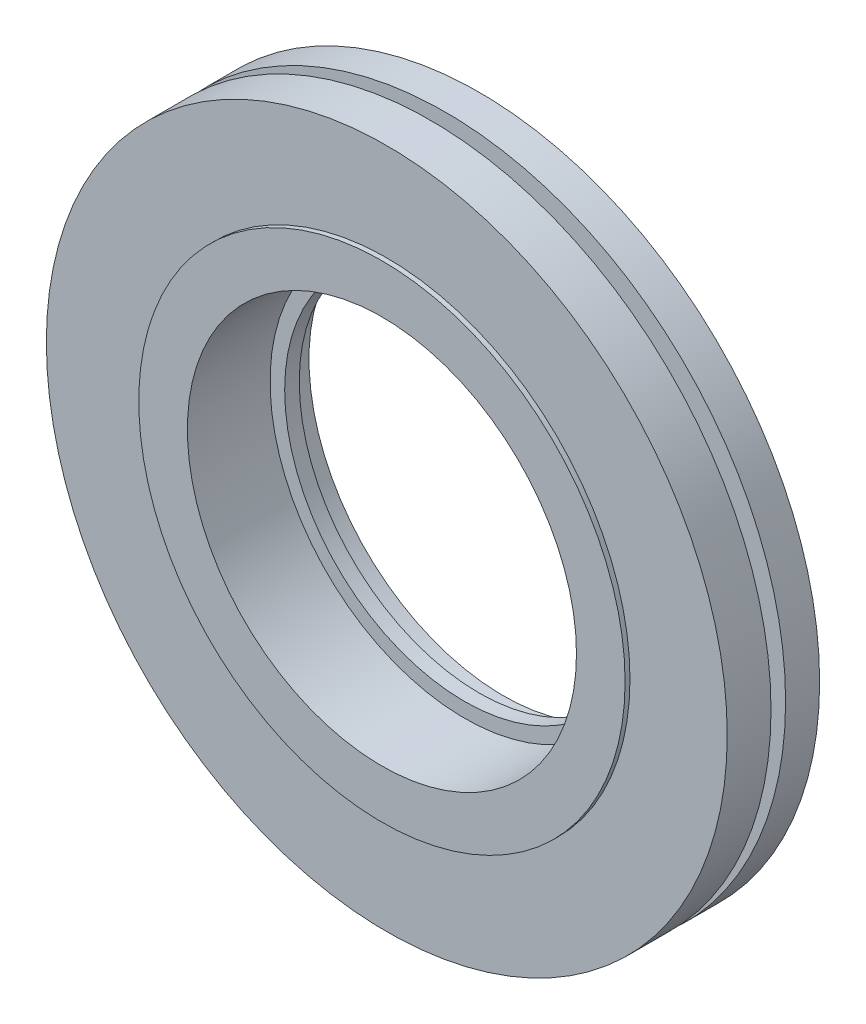
SolidWorks part; units mm, degrees
material "7075-T6 (SN)"
ref_plane "Front Plane" through (0, 0, 0) normal (0, 0, 1) x (1, 0, 0)
ref_plane "Top Plane" through (0, 0, 0) normal (0, 1, 0) x (1, 0, 0)
ref_plane "Right Plane" through (0, 0, 0) normal (1, 0, 0) x (0, 0, -1)
sketch "Sketch1" plane through (0, 0, 0) normal (0, 0, 1) x (1, 0, 0)
  circle A0 centre (0, 0) radius 5
  circle A1 centre (0, 0) radius 4
extrude "D10_Pilot_And_M10x0p5_Thread_Envelope" add sketch "Sketch1" along normal blind 2.5 from offset 1
sketch "Sketch2" plane through (0, 0, 0) normal (0, 0, 1) x (1, 0, 0)
  circle A0 centre (0, 0) radius 5
  circle A1 centre (0, 0) radius 3.7
extrude "Outer_Race_Inner_Shoulder_ID7p4" add sketch "Sketch2" along normal blind 0.3 from offset 1.5
sketch "Sketch3" plane through (0, 0, 0) normal (0, 0, 1) x (1, 0, 0)
  circle A0 centre (0, 0) radius 7
  circle A1 centre (0, 0) radius 3.7
extrude "Inboard_G10_Retention_Flange_H0p3" add sketch "Sketch3" along normal blind 0.3 from offset 1.5
sketch "Sketch4" plane through (0, 0, 0) normal (0, 0, 1) x (1, 0, 0)
  circle A0 centre (0, 0) radius 7
  circle A1 centre (0, 0) radius 4
extrude "M14x0p5_Bearing_Cap_Boss" add sketch "Sketch4" along normal blind 0.6 from offset 1.6
sketch "Sketch5" plane through (0, 0, 0) normal (0, 0, 1) x (1, 0, 0)
  circle A0 centre (0, 0) radius 7
  circle A1 centre (0, 0) radius 4.8
extrude "Flanged_Race_Pocket_D9p6" add sketch "Sketch5" along normal blind 0.9 from offset 2.5
sketch "Sketch6" plane through (0, 0, 1.8) normal (0, 0, 1) x (1, 0, 0)
  circle A0 centre (-6, 0) radius 0.6
  circle A1 centre (6, 0) radius 0.6
extrude "Two_Pin_Wrench_Holes_D1p2" cut sketch "Sketch6" against normal blind 0.301
